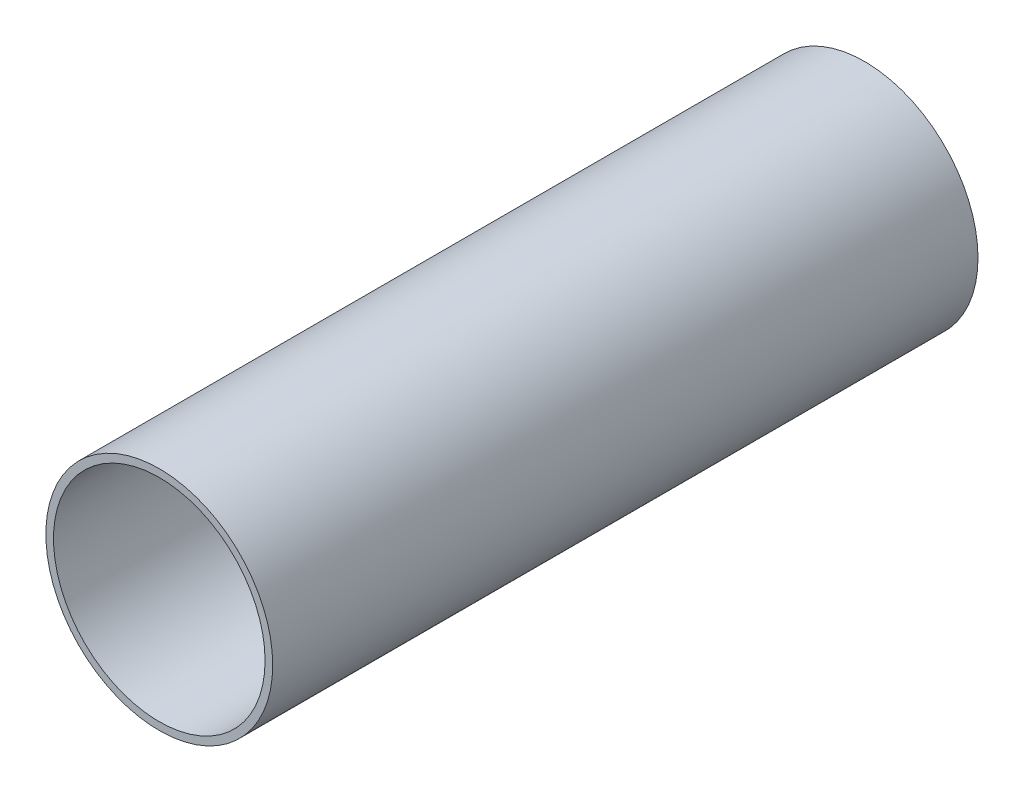
SolidWorks part; units mm, degrees
ref_plane "Front" through (0, 0, 0) normal (0, 0, 1) x (1, 0, 0)
ref_plane "Top" through (0, 0, 0) normal (0, 1, 0) x (1, 0, 0)
ref_plane "Right" through (0, 0, 0) normal (1, 0, 0) x (0, 0, -1)
sketch "Sketch1" plane through (0, 0, 0) normal (0, 0, 1) x (1, 0, 0)
  circle A0 centre (0, 0) radius 9.65
  circle A1 centre (0, 0) radius 9
  dimension "D1" = 19.3
  dimension "D2" = 18
extrude "Boss-Extrude1" add sketch "Sketch1" along normal blind 60
